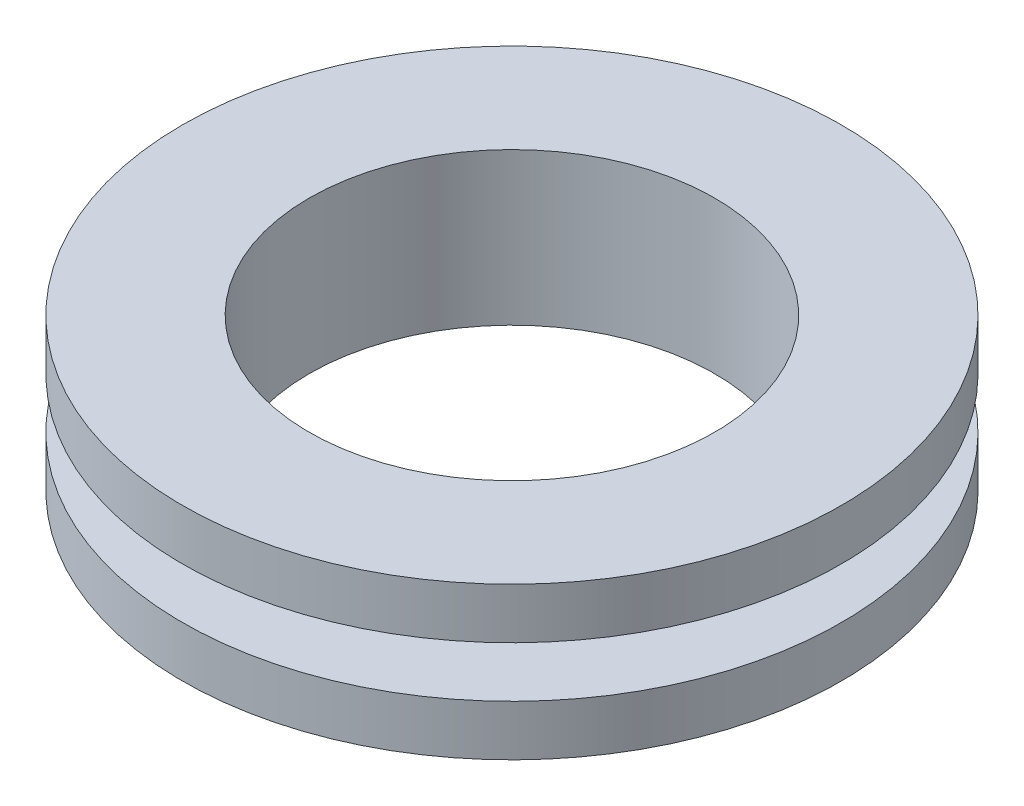
SolidWorks part; units mm, degrees
ref_plane "Plan de face" through (0, 0, 0) normal (0, 0, 1) x (1, 0, 0)
ref_plane "Plan de dessus" through (0, 0, 0) normal (0, 1, 0) x (1, 0, 0)
ref_plane "Plan de droite" through (0, 0, 0) normal (1, 0, 0) x (0, 0, -1)
sketch "Sketch1" plane through (0, 0, 0) normal (0, 0, 1) x (1, 0, 0)
  line L0 (0, 3.8002) -> (0, -3.8582) construction
  line L8 (5, 0.5) -> (5, -0.5)
  line L9 (5, -0.5) -> (6.5, -0.5)
  line L10 (6.5, -0.5) -> (6.5, -1.5)
  line L12 (5, 0.5) -> (6.5, 0.5)
  line L13 (6.5, 0.5) -> (6.5, 1.5)
  line L20 (6.5, 1.5) -> (4, 1.5)
  line L23 (4, 1.5) -> (4, -1.5)
  line L26 (4, -1.5) -> (6.5, -1.5)
  point P5 (5, 0)
  dimension "D3" = 1.5
  dimension "D5" = 4
  dimension "D1" = 5
  dimension "D2" = 1
  dimension "D7" = 3
revolve "Revolve1" add sketch "Sketch1" angle 360 about L0
